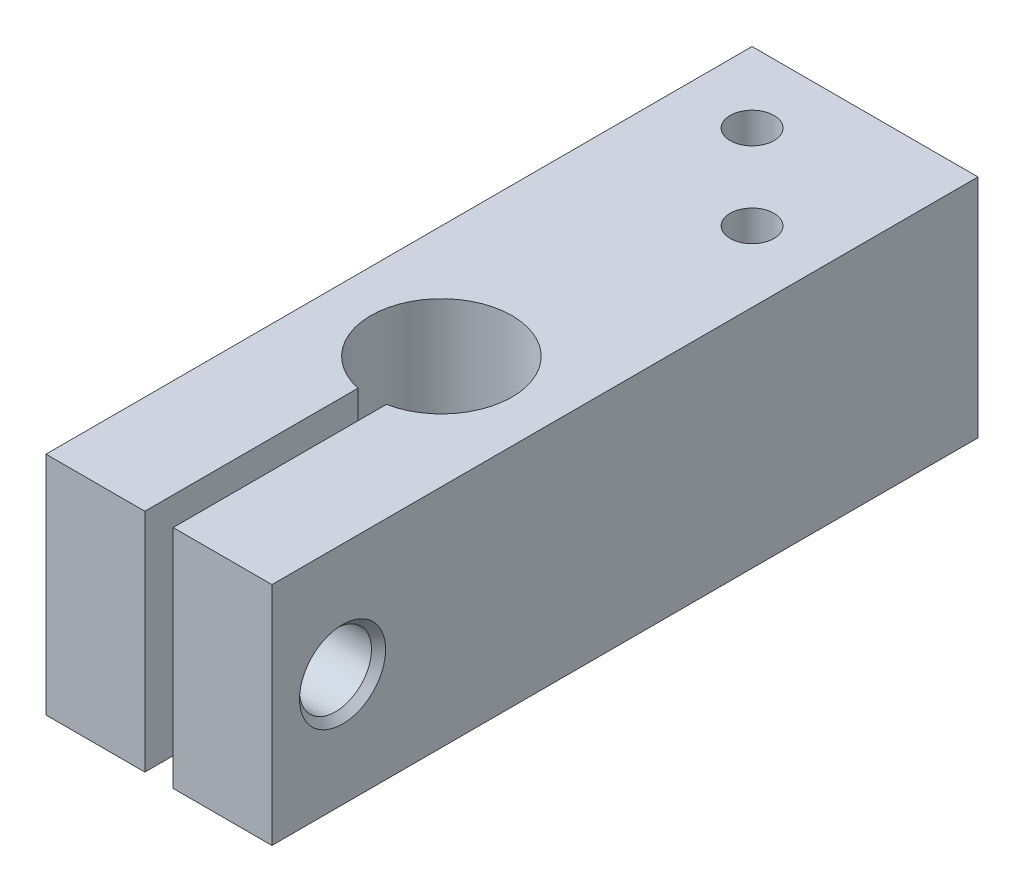
SolidWorks part; units mm, degrees
material "6063-T6"
ref_plane "Front Plane" through (0, 0, 0) normal (0, 0, 1) x (1, 0, 0)
ref_plane "Top Plane" through (0, 0, 0) normal (0, 1, 0) x (1, 0, 0)
ref_plane "Right Plane" through (0, 0, 0) normal (1, 0, 0) x (0, 0, -1)
sketch "Sketch1" plane through (0, 0, 0) normal (0, 0, 1) x (1, 0, 0)
  line L1 (8, -8) -> (-8, -8)
  line L2 (8, -8) -> (8, 8)
  line L3 (8, 8) -> (-8, 8)
  line L4 (-8, -8) -> (-8, 8)
  line L5 (8, -8) -> (-8, 8) construction
  line L6 (8, 8) -> (-8, -8) construction
  point P0 (0, 0)
  dimension "D1" = 16
  dimension "D2" = 16
extrude "Base" add sketch "Sketch1" along normal blind 50
sketch "Sketch2" plane through (0, 8, 0) normal (0, 1, 0) x (1, 0, 0)
  line L0 (-1, -50) -> (-1, -34.899)
  line L1 (8, -50) -> (-8, -50) construction
  line L2 (1, -50) -> (1, -34.899)
  line L3 (0, 0) -> (0, -9.2456) construction
  circle A0 centre (0, -30) radius 5
  line M6 (-8, -50) -> (8, -50)
  dimension "D1" = 10
  dimension "D2" = 20
  dimension "D3" = 2
extrude "RodSlot" cut sketch "Sketch2" against normal through all contours A0 | A0 L0 L2 M6
sketch "Sketch3" plane through (8, 0, 0) normal (1, 0, 0) x (0, 0, -1)
  line L0 (-50, -8) -> (-50, 8) construction
  circle A0 centre (-45, 0) radius 2.55
  dimension "D1" = 5.1
  dimension "D2" = 5
extrude "RodSlotScrew" cut sketch "Sketch3" against normal up to next
chamfer "Chamfer1" distance 0.5 angle 45 1 edges at (8, 0, 42.45)
hole_wizard "M5x0.8 Tapped Hole for rod screw" positions "Sketch4" profile "Sketch5" tap size "M5x0.8" standard "ANSI Metric"
sketch "Sketch4" plane through (-8, 0, 0) normal (-1, 0, 0) x (0, 0, 1)
  point P0 (45, 0)
cosmetic thread "Hole Thread1" parameters "D1"=3.8, "D2"=5
sketch "Sketch5" plane through (-8, 0, 45) normal (0, 1, 0) x (0, 0, 1)
  line L0 (0, 0) -> (0, 8.9)
  line L1 (0, 8.9) -> (2.1, 7.6382)
  line L2 (2.1, 7.6382) -> (2.1, 0)
  line L5 (2.1, 0) -> (0, 0)
  line L10 (0, 8.9) -> (-2.1, 7.6382) construction
  line L11 (0, -6.35) -> (0, 107.95) construction
  dimension "Tap Drill Dia." = 4.2
  dimension "Tap Drill Depth" = 8.9
  dimension "Drill Angle" = 118
sketch "Sketch6" plane through (0, -8, 0) normal (0, -1, 0) x (1, 0, 0)
  line L0 (-8, 0) -> (8, 16) construction
  line L1 (8, 50) -> (8, 0) construction
  line L2 (8, 16) -> (8, 0) construction
  line L3 (-8, 0) -> (8, 0) construction
  circle A0 centre (3, 11) radius 1.55
  circle A1 centre (-3, 5) radius 1.55
  dimension "D1" = 3.1
  dimension "D2" = 3
  dimension "D3" = 3
extrude "ScrewsHoles" cut sketch "Sketch6" against normal through all
equation "\"D2@Sketch1\"=\"D1@Sketch1\""
